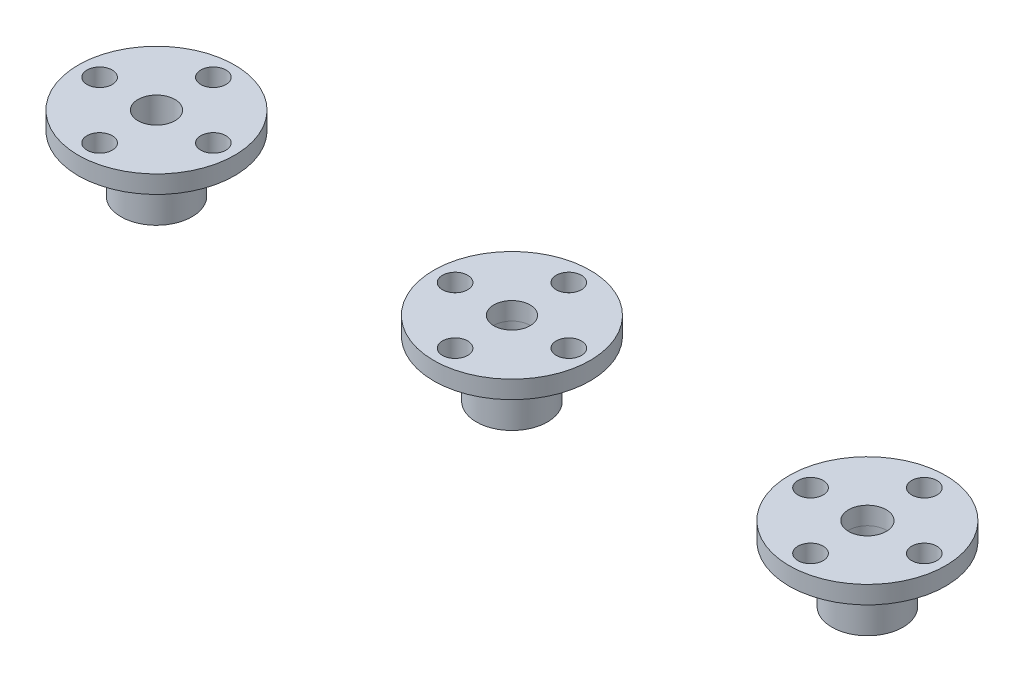
SolidWorks part; units mm, degrees
ref_plane "前视基准面" through (0, 0, 0) normal (0, 0, 1) x (1, 0, 0)
ref_plane "上视基准面" through (0, 0, 0) normal (0, 1, 0) x (1, 0, 0)
ref_plane "右视基准面" through (0, 0, 0) normal (1, 0, 0) x (0, 0, -1)
sketch "草图1" plane through (0, 0, 0) normal (0, 1, 0) x (1, 0, 0)
  circle A0 centre (0, 0) radius 2.55
  circle A1 centre (0, 0) radius 5
  circle A2 centre (-50, 0) radius 2.6
  circle A3 centre (-50, 0) radius 5
  circle A4 centre (50, 0) radius 2.65
  circle A5 centre (50, 0) radius 5
  dimension "D1" = 5.1
  dimension "D2" = 10
  dimension "D3" = 5.2
  dimension "D4" = 10
  dimension "D5" = 5.3
  dimension "D6" = 10
  dimension "D7" = 50
  dimension "D8" = 50
extrude "凸台-拉伸1" add sketch "草图1" along normal blind 8
ref_plane "基准面1" through (0, 8, 0) normal (0, 1, 0) x (1, 0, 0)
sketch "草图3" plane through (0, 8, 0) normal (0, 1, 0) x (1, 0, 0)
  circle A0 centre (-50, 0) radius 2.6
  circle A1 centre (-50, 0) radius 8 construction
  circle A2 centre (-50, 0) radius 11
  circle A3 centre (-50, 8) radius 1.775
  circle A4 centre (-42, 0) radius 1.775
  circle A5 centre (-50, -8) radius 1.775
  circle A6 centre (-58, 0) radius 1.775
  circle A7 centre (0, 0) radius 2.55
  circle A8 centre (0, 0) radius 8 construction
  circle A9 centre (0, 0) radius 11
  circle A10 centre (50, 0) radius 2.65
  circle A11 centre (50, 0) radius 8 construction
  circle A12 centre (50, 0) radius 11
  circle A14 centre (0, 8) radius 1.775
  circle A15 centre (8, 0) radius 1.775
  circle A16 centre (0, -8) radius 1.775
  circle A17 centre (-8, 0) radius 1.775
  circle A18 centre (50, 8) radius 1.775
  circle A19 centre (58, 0) radius 1.775
  circle A20 centre (50, -8) radius 1.775
  circle A21 centre (42, 0) radius 1.775
  point P16 (-50, 0)
  point P35 (0, 0)
  point P44 (50, 0)
  dimension "D1" = 22
  dimension "D2" = 5.2
  dimension "D3" = 16
  dimension "D4" = 3.55
  dimension "D6" = 22
  dimension "D7" = 22
  dimension "D8" = 16
  dimension "D9" = 16
  dimension "D10" = 5.1
  dimension "D11" = 5.3
  dimension "D12" = 3.55
  dimension "D14" = 3.55
  dimension "D5" = 4
  dimension "D13" = 4
  dimension "D15" = 4
extrude "凸台-拉伸2" add sketch "草图3" along normal blind 2.5
